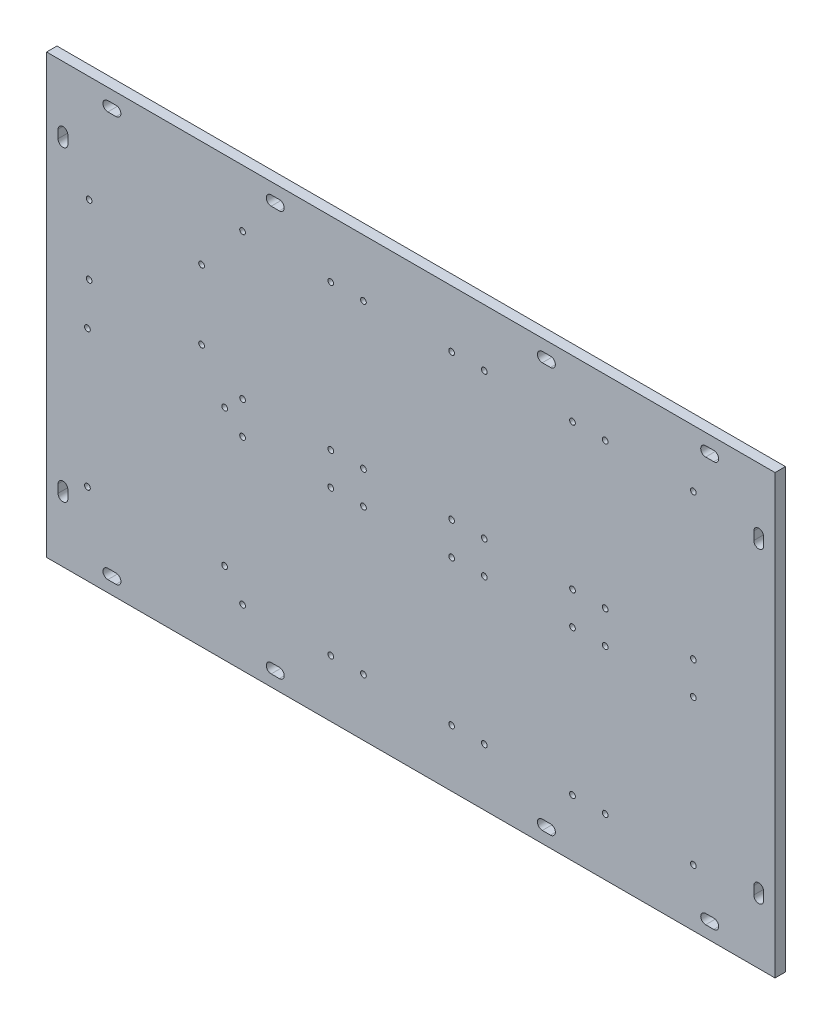
SolidWorks part; units mm, degrees
material "Acrylic (Medium-high impact)"
ref_plane "Front Plane" through (0, 0, 0) normal (0, 0, 1) x (1, 0, 0)
ref_plane "Top Plane" through (0, 0, 0) normal (0, 1, 0) x (1, 0, 0)
ref_plane "Right Plane" through (0, 0, 0) normal (1, 0, 0) x (0, 0, -1)
sketch "Sketch1" plane through (0, 0, 0) normal (0, 0, 1) x (1, 0, 0)
  line L5 (223, -134) -> (-223, -134)
  line L6 (223, -134) -> (223, 134)
  line L11 (223, 134) -> (-223, 134)
  line L12 (-223, -134) -> (-223, 134)
  line L17 (223, -134) -> (-223, 134) construction
  line L18 (223, 134) -> (-223, -134) construction
  point P0 (0, 0)
  dimension "D1" = 446
  dimension "D2" = 268
extrude "Boss-Extrude1" add sketch "Sketch1" along normal blind 6.35
ref_plane "Plane1" through (-223, -134, 6.35) normal (0, -1, 0) x (-1, 0, 0)
sketch "Sketch3" plane through (0, 0, 6.35) normal (0, 0, 1) x (1, 0, 0)
  line L1 (-196.93, 68.72) -> (-128.1, 68.72) construction
  line L2 (-196.93, 68.72) -> (-196.93, 26.3) construction
  line L3 (-196.93, 26.3) -> (-128.1, 26.3) construction
  line L4 (-128.1, 68.72) -> (-128.1, 26.3) construction
  line L5 (-196.93, 68.72) -> (-128.1, 26.3) construction
  line L6 (-196.93, 26.3) -> (-128.1, 68.72) construction
  line L8 (-185.5, 124) -> (-180.5, 124) construction
  line L9 (-185.5, 127) -> (-180.5, 127)
  line L10 (-185.5, 121) -> (-180.5, 121)
  line L11 (-223, 134) -> (-223, -134) construction
  line L12 (-213, 124) -> (-213, -124)
  line L13 (-213, -124) -> (213, -124)
  line L14 (213, -124) -> (213, 124)
  line L15 (213, 124) -> (-213, 124)
  line L16 (-213, 124) -> (-213, -124) construction
  line L17 (-213, -124) -> (213, -124) construction
  line L18 (213, -124) -> (213, 124) construction
  line L19 (213, 124) -> (-213, 124) construction
  line L20 (-213, 96.5) -> (-213, 91.5) construction
  line L21 (-210, 96.5) -> (-210, 91.5)
  line L22 (-216, 96.5) -> (-216, 91.5)
  line L23 (223, 134) -> (-223, 134) construction
  line L24 (-85.5, 124) -> (-80.5, 124) construction
  line L25 (-85.5, 127) -> (-80.5, 127)
  line L26 (-85.5, 121) -> (-80.5, 121)
  line L27 (0, 18.5089) -> (0, -17.6134) construction
  line L28 (-18.9112, 0) -> (16.6467, 0) construction
  line L29 (85.5, 124) -> (80.5, 124) construction
  line L30 (85.5, 127) -> (80.5, 127)
  line L31 (85.5, 121) -> (80.5, 121)
  line L32 (185.5, 124) -> (180.5, 124) construction
  line L33 (185.5, 127) -> (180.5, 127)
  line L34 (185.5, 121) -> (180.5, 121)
  line L35 (213, 96.5) -> (213, 91.5) construction
  line L36 (210, 96.5) -> (210, 91.5)
  line L37 (216, 96.5) -> (216, 91.5)
  line L38 (213, -96.5) -> (213, -91.5) construction
  line L39 (210, -96.5) -> (210, -91.5)
  line L40 (216, -96.5) -> (216, -91.5)
  line L41 (185.5, -124) -> (180.5, -124) construction
  line L42 (185.5, -127) -> (180.5, -127)
  line L43 (185.5, -121) -> (180.5, -121)
  line L44 (85.5, -124) -> (80.5, -124) construction
  line L45 (85.5, -127) -> (80.5, -127)
  line L46 (85.5, -121) -> (80.5, -121)
  line L47 (-85.5, -124) -> (-80.5, -124) construction
  line L48 (-85.5, -127) -> (-80.5, -127)
  line L49 (-85.5, -121) -> (-80.5, -121)
  line L50 (-185.5, -124) -> (-180.5, -124) construction
  line L51 (-185.5, -127) -> (-180.5, -127)
  line L52 (-185.5, -121) -> (-180.5, -121)
  line L53 (-213, -96.5) -> (-213, -91.5) construction
  line L54 (-210, -96.5) -> (-210, -91.5)
  line L55 (-216, -96.5) -> (-216, -91.5)
  line L56 (223, -134) -> (223, 134) construction
  line L57 (119, 10) -> (173, 10) construction
  line L58 (119, 10) -> (119, 99) construction
  line L59 (119, 99) -> (173, 99) construction
  line L60 (173, 10) -> (173, 99) construction
  line L61 (119, 10) -> (173, 99) construction
  line L62 (119, 99) -> (173, 10) construction
  line L63 (119, -99) -> (173, -10) construction
  line L64 (119, -10) -> (173, -99) construction
  line L65 (173, -10) -> (173, -99) construction
  line L66 (119, -99) -> (173, -99) construction
  line L67 (119, -10) -> (119, -99) construction
  line L68 (119, -10) -> (173, -10) construction
  line L69 (-223, -134) -> (223, -134) construction
  line L70 (-114, -84) -> (-198, -84) construction
  line L71 (-114, -84) -> (-114, 0) construction
  line L72 (-114, 0) -> (-198, 0) construction
  line L73 (-198, -84) -> (-198, 0) construction
  line L74 (-114, -84) -> (-198, 0) construction
  line L75 (-114, 0) -> (-198, -84) construction
  arc A0 (-185.5, 127) -> (-185.5, 121) centre (-185.5, 124) ccw
  arc A1 (-180.5, 121) -> (-180.5, 127) centre (-180.5, 124) ccw
  arc A2 (-210, 96.5) -> (-216, 96.5) centre (-213, 96.5) ccw
  arc A3 (-216, 91.5) -> (-210, 91.5) centre (-213, 91.5) ccw
  arc A4 (-85.5, 127) -> (-85.5, 121) centre (-85.5, 124) ccw
  arc A5 (-80.5, 121) -> (-80.5, 127) centre (-80.5, 124) ccw
  arc A6 (85.5, 127) -> (85.5, 121) centre (85.5, 124) cw
  arc A7 (80.5, 121) -> (80.5, 127) centre (80.5, 124) cw
  arc A8 (185.5, 127) -> (185.5, 121) centre (185.5, 124) cw
  arc A9 (180.5, 121) -> (180.5, 127) centre (180.5, 124) cw
  arc A10 (210, 96.5) -> (216, 96.5) centre (213, 96.5) cw
  arc A11 (216, 91.5) -> (210, 91.5) centre (213, 91.5) cw
  arc A12 (210, -96.5) -> (216, -96.5) centre (213, -96.5) ccw
  arc A13 (216, -91.5) -> (210, -91.5) centre (213, -91.5) ccw
  arc A14 (185.5, -127) -> (185.5, -121) centre (185.5, -124) ccw
  arc A15 (180.5, -121) -> (180.5, -127) centre (180.5, -124) ccw
  arc A16 (85.5, -127) -> (85.5, -121) centre (85.5, -124) ccw
  arc A17 (80.5, -121) -> (80.5, -127) centre (80.5, -124) ccw
  arc A18 (-85.5, -127) -> (-85.5, -121) centre (-85.5, -124) cw
  arc A19 (-80.5, -121) -> (-80.5, -127) centre (-80.5, -124) cw
  arc A20 (-185.5, -127) -> (-185.5, -121) centre (-185.5, -124) cw
  arc A21 (-180.5, -121) -> (-180.5, -127) centre (-180.5, -124) cw
  arc A22 (-210, -96.5) -> (-216, -96.5) centre (-213, -96.5) cw
  arc A23 (-216, -91.5) -> (-210, -91.5) centre (-213, -91.5) cw
  circle A25 centre (119, 10) radius 1.75
  circle A26 centre (173, 10) radius 1.75
  circle A27 centre (119, 99) radius 1.75
  circle A28 centre (173, 99) radius 1.75
  circle A29 centre (99, 99) radius 1.75
  circle A30 centre (99, 10) radius 1.75
  circle A31 centre (45, 10) radius 1.75
  circle A32 centre (45, 99) radius 1.75
  circle A33 centre (25, 99) radius 1.75
  circle A34 centre (25, 10) radius 1.75
  circle A35 centre (-29, 10) radius 1.75
  circle A36 centre (-29, 99) radius 1.75
  circle A37 centre (-49, 99) radius 1.75
  circle A38 centre (-49, 10) radius 1.75
  circle A39 centre (-103, 10) radius 1.75
  circle A40 centre (-103, 99) radius 1.75
  circle A41 centre (-103, -99) radius 1.75
  circle A42 centre (-103, -10) radius 1.75
  circle A43 centre (-49, -10) radius 1.75
  circle A44 centre (-49, -99) radius 1.75
  circle A45 centre (-29, -99) radius 1.75
  circle A46 centre (-29, -10) radius 1.75
  circle A47 centre (25, -10) radius 1.75
  circle A48 centre (25, -99) radius 1.75
  circle A49 centre (45, -99) radius 1.75
  circle A50 centre (45, -10) radius 1.75
  circle A51 centre (99, -10) radius 1.75
  circle A52 centre (99, -99) radius 1.75
  circle A53 centre (173, -99) radius 1.75
  circle A54 centre (119, -99) radius 1.75
  circle A55 centre (173, -10) radius 1.75
  circle A56 centre (119, -10) radius 1.75
  circle A57 centre (-198, 0) radius 1.75
  circle A58 centre (-114, 0) radius 1.75
  circle A59 centre (-198, -84) radius 1.75
  circle A60 centre (-114, -84) radius 1.75
  circle A61 centre (-196.93, 26.3) radius 1.75
  circle A62 centre (-128.1, 26.3) radius 1.75
  circle A63 centre (-128.1, 68.72) radius 1.75
  circle A64 centre (-196.93, 68.72) radius 1.75
  point P3 (-183, 124)
  point P15 (-213, 94)
  point P26 (-83, 124)
  point P36 (83, 124)
  point P43 (183, 124)
  point P50 (213, 94)
  point P57 (213, -94)
  point P64 (183, -124)
  point P71 (83, -124)
  point P78 (-83, -124)
  point P85 (-183, -124)
  point P92 (-213, -94)
  point P97 (146, 54.5)
  point P164 (146, -54.5)
  point P165 (-156, -42)
  point P176 (-162.515, 47.51)
  dimension "D3" = 3
  dimension "D6" = 3
  dimension "D13" = 3.5
  dimension "D23" = 3.5
  dimension "D2" = 5
  dimension "D4" = 40
  dimension "D5" = 5
  dimension "D7" = 40
  dimension "D9" = 50
  dimension "D10" = 89
  dimension "D11" = 54
  dimension "D12" = 10
  dimension "D15" = 84
  dimension "D16" = 84
  dimension "D17" = 25
  dimension "D18" = 50
  dimension "D19" = 42.42
  dimension "D20" = 68.83
  dimension "D21" = 26.3
  dimension "D22" = 1.07
  dimension "D1" = 10
  dimension "D8" = 2
  dimension "D14" = 4
extrude "Cut-Extrude1" cut sketch "Sketch3" against normal through all
